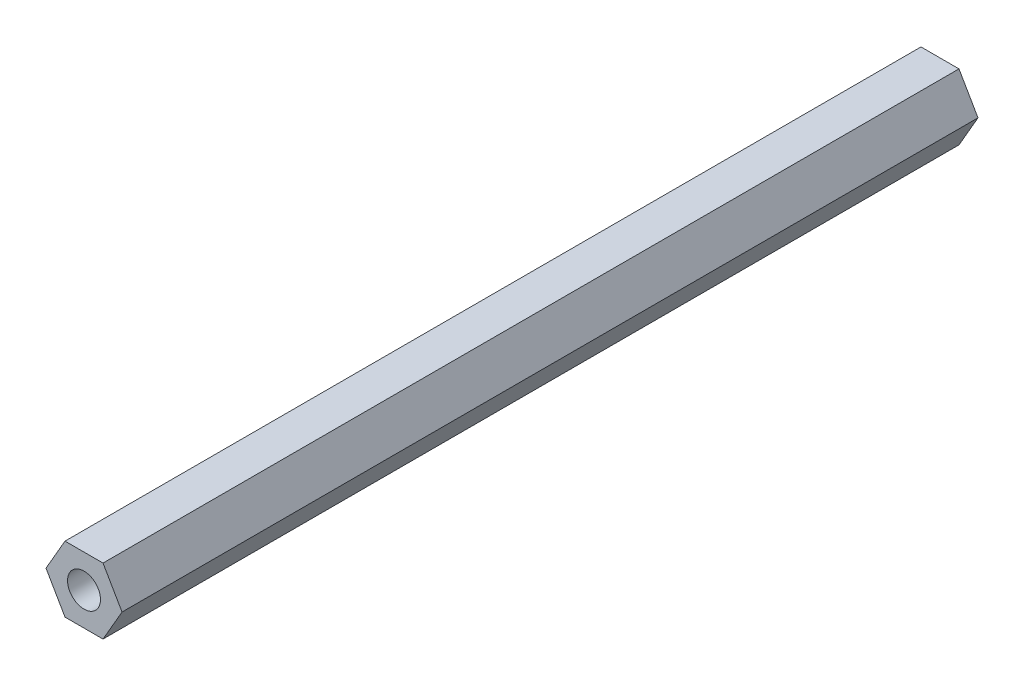
SolidWorks part; units mm, degrees
ref_plane "前视基准面" through (0, 0, 0) normal (0, 0, 1) x (1, 0, 0)
ref_plane "上视基准面" through (0, 0, 0) normal (0, 1, 0) x (1, 0, 0)
ref_plane "右视基准面" through (0, 0, 0) normal (1, 0, 0) x (0, 0, -1)
sketch "草图1" plane through (0, 0, 0) normal (0, 0, 1) x (1, 0, 0)
  line L1 (2.8868, 0) -> (1.4434, 2.5)
  line L2 (1.4434, 2.5) -> (-1.4434, 2.5)
  line L3 (-1.4434, 2.5) -> (-2.8868, 0)
  line L4 (-2.8868, 0) -> (-1.4434, -2.5)
  line L5 (-1.4434, -2.5) -> (1.4434, -2.5)
  line L6 (1.4434, -2.5) -> (2.8868, 0)
  circle A0 centre (0, 0) radius 2.5 construction
  circle A1 centre (0, 0) radius 1.5
  dimension "D2" = 3
  dimension "D1" = 5
extrude "凸台-拉伸1" add sketch "草图1" along normal blind 65 contours A1 | L5 L6 L1 L2 L3 L4 A1
hole_wizard "M3 螺纹孔1" positions "草图2" profile "草图3" tap size "M3" standard "GB"
sketch "草图2" plane through (0, 0, 65) normal (0, 0, 1) x (1, 0, 0)
  point P0 (0, 0)
sketch "草图3" plane through (0, 0, 65) normal (1, 0, 0) x (0, -1, 0)
  line L0 (0, 0) -> (0, 8.2511)
  line L1 (0, 8.2511) -> (1.25, 7.5)
  line L2 (1.25, 7.5) -> (1.25, 0)
  line L5 (1.25, 0) -> (0, 0)
  line L10 (0, 8.2511) -> (-1.25, 7.5) construction
  line L11 (0, -6.35) -> (0, 107.95) construction
  dimension "螺纹孔钻头直径" = 2.5
  dimension "螺纹孔钻头深度" = 7.5
  dimension "导头角度" = 118
cosmetic thread "孔螺蚊线1" parameters "D1"=6, "D2"=3
